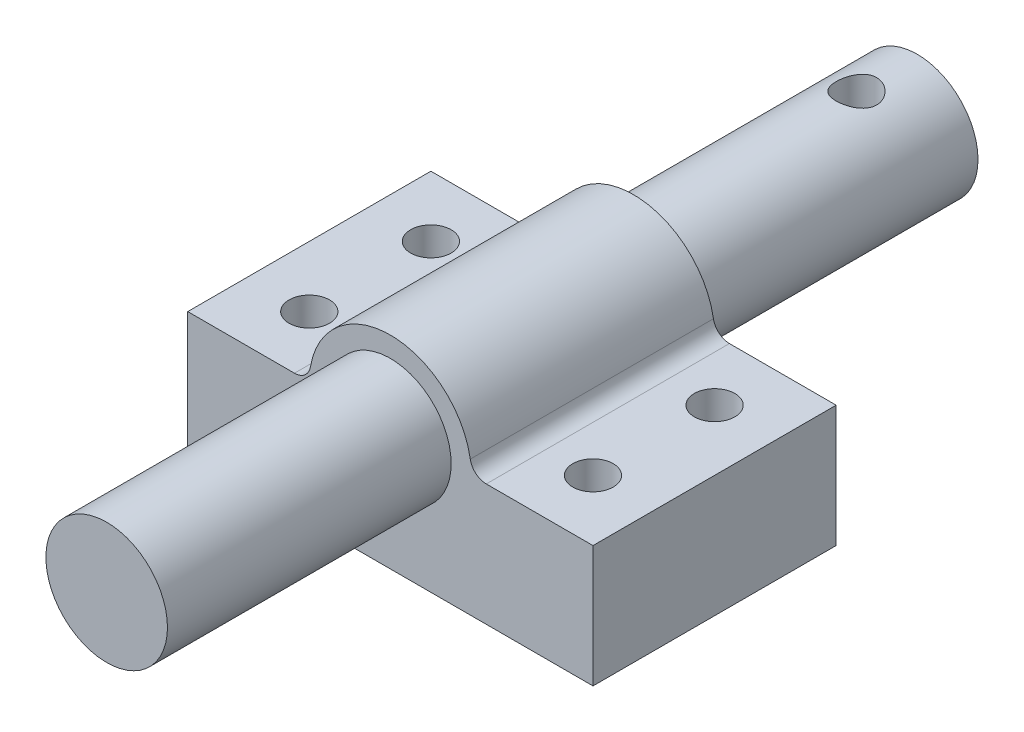
SolidWorks part; units mm, degrees
ref_plane "Front Plane" through (0, 0, 0) normal (0, 0, 1) x (1, 0, 0)
ref_plane "Top Plane" through (0, 0, 0) normal (0, 1, 0) x (1, 0, 0)
ref_plane "Right Plane" through (0, 0, 0) normal (1, 0, 0) x (0, 0, -1)
sketch "Sketch1" plane through (0, 0, 0) normal (0, 1, 0) x (1, 0, 0)
  line L0 (0, 90) -> (0, 100)
  line L1 (2, 100) -> (7.5, 100)
  line L2 (7.5, 100) -> (7.5, 65)
  line L3 (7.5, 65) -> (9, 65)
  line L4 (9, 65) -> (9, 35)
  line L5 (7.5, 35) -> (9, 35)
  line L6 (7.5, 35) -> (7.5, 0)
  line L7 (7.5, 0) -> (0, 0)
  line L8 (0, 0) -> (0, 90)
  line L9 (0, 100) -> (2, 100)
revolve "Revolve1" add sketch "Sketch1" angle 360 about L0
ref_plane "Plane1" through (0, 0, -50) normal (0, 0, 1) x (1, 0, 0)
sketch "Sketch5" plane through (0, 0, -50) normal (0, 0, 1) x (1, 0, 0)
  line L2 (-25, -10) -> (-25, -15)
  line L3 (-25, -15) -> (25, -15)
  line L6 (25, -10) -> (25, 0)
  line L7 (20, 0) -> (12.5, 0)
  line L8 (25, 0) -> (20, 0)
  line L9 (-20, 0) -> (-12.5, 0)
  line L10 (-25, -10) -> (-25, 0)
  line L11 (-25, 0) -> (-20, 0)
  line L12 (-12.5, 0) -> (-11.8322, 0)
  line L13 (12.5, 0) -> (11.8322, 0)
  line L14 (25, -15) -> (25, -10)
  arc A0 (9.8601, 1.6667) -> (-9.8601, 1.6667) centre (0, 0) ccw
  arc A1 (11.8322, 0) -> (9.8601, 1.6667) centre (11.8322, 2) cw
  arc A2 (-11.8322, 0) -> (-9.8601, 1.6667) centre (-11.8322, 2) ccw
  point P13 (10, 0)
  point P20 (-10, 0)
  dimension "D1" = 2
extrude "Boss-Extrude1" add sketch "Sketch5" against normal blind 15 and the other way blind 15
sketch "Sketch6" plane through (0, 0, 0) normal (0, 1, 0) x (1, 0, 0)
  line L0 (-25, 65) -> (-17.5, 65) construction
  line L1 (-11.8322, 65) -> (-25, 65) construction
  line L2 (-17.5, 65) -> (-17.5, 57.5) construction
  circle A0 centre (-17.5, 57.5) radius 2.5
  circle A1 centre (17.5, 57.5) radius 2.5
  circle A2 centre (17.5, 42.5) radius 2.5
  circle A3 centre (-17.5, 42.5) radius 2.5
extrude "Cut-Extrude2" cut sketch "Sketch6" against normal blind 25
sketch "Sketch8" plane through (0, 0, 0) normal (0, 1, 0) x (1, 0, 0)
  line L0 (0, 100) -> (0, 92.5) construction
  line L1 (7.5, 100) -> (-7.5, 100) construction
  circle A0 centre (0, 92.5) radius 2.5
extrude "Cut-Extrude3" cut sketch "Sketch8" along normal blind 35 and the other way blind 30
